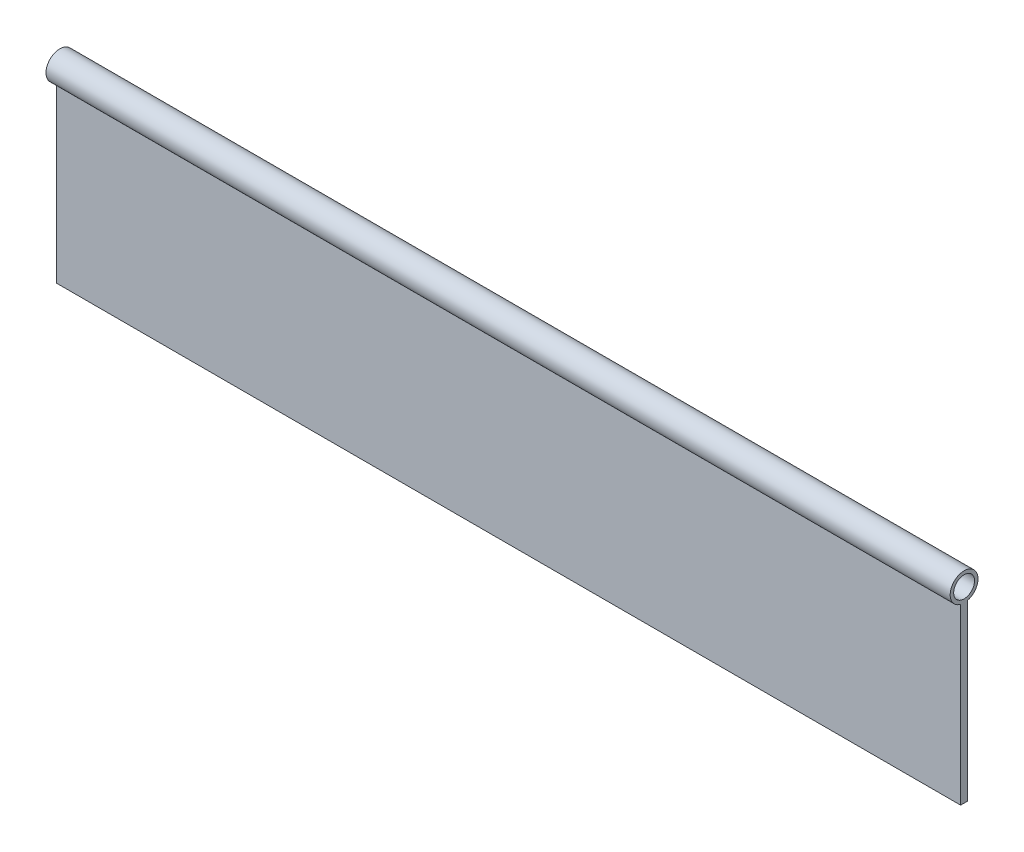
SolidWorks part; units mm, degrees
ref_plane "Front Plane" through (0, 0, 0) normal (0, 0, 1) x (1, 0, 0)
ref_plane "Top Plane" through (0, 0, 0) normal (0, 1, 0) x (1, 0, 0)
ref_plane "Right Plane" through (0, 0, 0) normal (1, 0, 0) x (0, 0, -1)
sketch "Sketch1" plane through (0, 0, 0) normal (1, 0, 0) x (0, 0, -1)
  line L0 (0, 0) -> (0, -7.3444) construction
  line L3 (-1, -3.873) -> (-1, -53.873)
  line L4 (-1, -53.873) -> (1, -53.873)
  line L5 (1, -3.873) -> (1, -53.873)
  arc A0 (1, -3.873) -> (-1, -3.873) centre (0, 0) ccw
  circle A1 centre (0, 0) radius 3
  dimension "D1" = 8
  dimension "D2" = 6
  dimension "D3" = 2
  dimension "D4" = 1
  dimension "D5" = 50
extrude "Boss-Extrude1" add sketch "Sketch1" along normal blind 260
